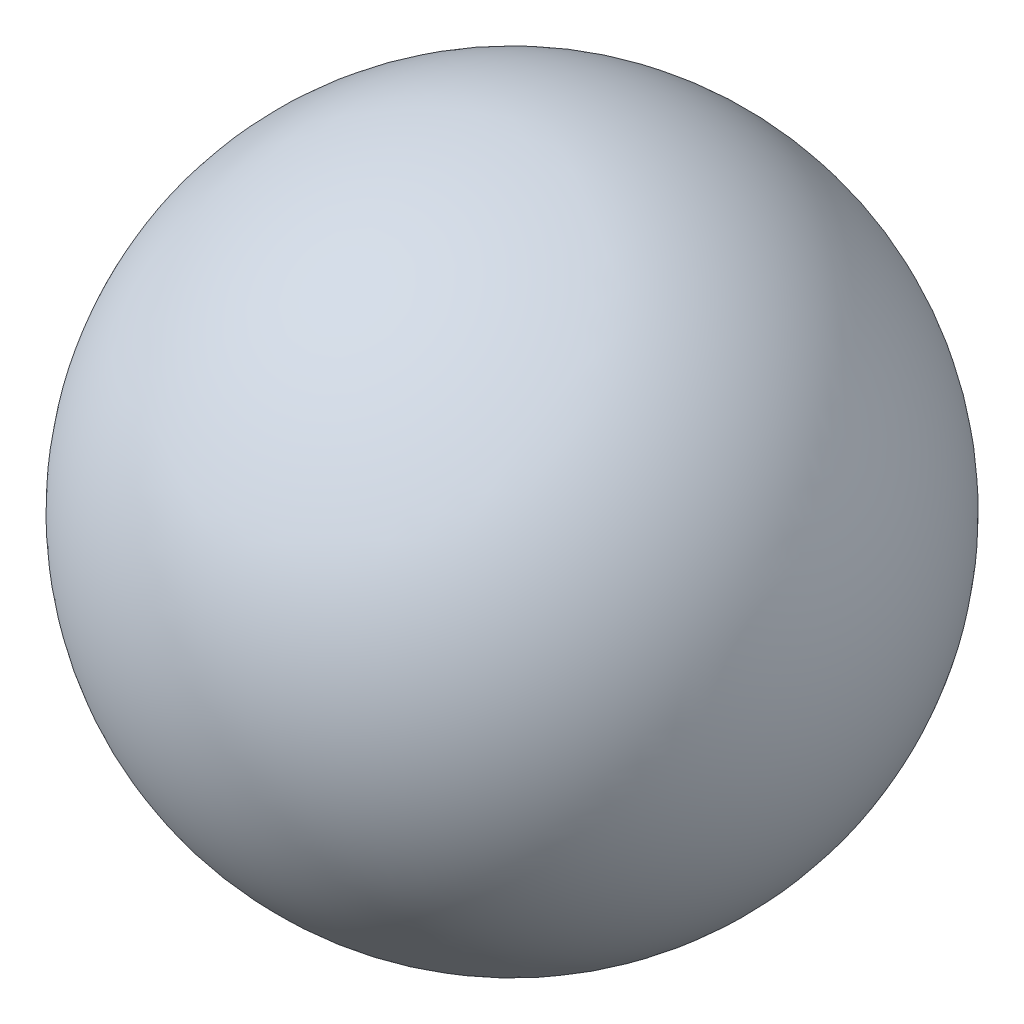
SolidWorks part; units mm, degrees
ref_plane "Front Plane" through (0, 0, 0) normal (0, 0, 1) x (1, 0, 0)
ref_plane "Top Plane" through (0, 0, 0) normal (0, 1, 0) x (1, 0, 0)
ref_plane "Right Plane" through (0, 0, 0) normal (1, 0, 0) x (0, 0, -1)
sketch "Sketch1" plane through (0, 0, 0) normal (0, 0, 1) x (1, 0, 0)
  line L0 (-12, 0) -> (12, 0)
  line L1 (0, 0) -> (-14.0781, 0) construction
  arc A0 (-12, 0) -> (12, 0) centre (0, 0) ccw
  point P4 (0, 0)
  dimension "D1" = 24
revolve "Revolve1" add sketch "Sketch1" angle 360 about L1
